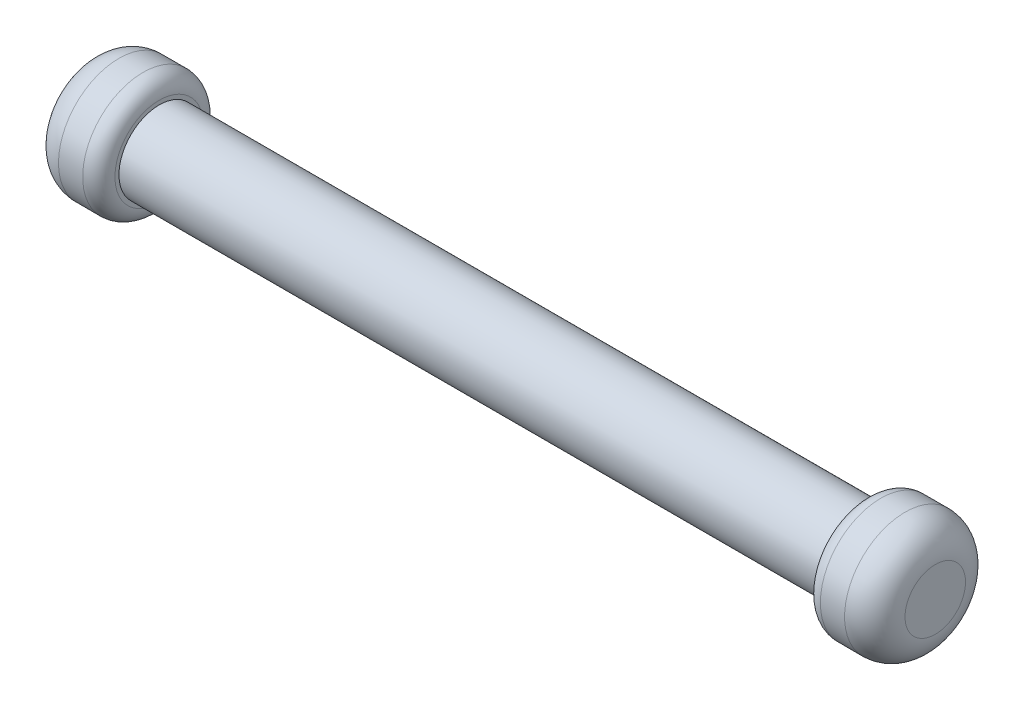
SolidWorks part; units mm, degrees
material "Ст3пс ГОСТ 380-94"
ref_plane "Front Plane" through (0, 0, 0) normal (0, 0, 1) x (1, 0, 0)
ref_plane "Top Plane" through (0, 0, 0) normal (0, 1, 0) x (1, 0, 0)
ref_plane "Right Plane" through (0, 0, 0) normal (1, 0, 0) x (0, 0, -1)
sketch "Эскиз1" plane through (0, 0, 0) normal (0, 0, 1) x (1, 0, 0)
  line L0 (0, 0) -> (0, 3)
  line L1 (0, 3) -> (3.5, 3)
  line L2 (3.5, 3) -> (3.5, 2)
  line L3 (3.5, 2) -> (38.5, 2)
  line L4 (38.5, 2) -> (38.5, 3)
  line L5 (38.5, 3) -> (42, 3)
  line L6 (42, 3) -> (42, 0)
  line L7 (42, 0) -> (0, 0)
  line L8 (0, 0) -> (-3.168, 0) construction
  dimension "D1" = 4
  dimension "D2" = 6
  dimension "D3" = 6
  dimension "D4" = 3.5
  dimension "D5" = 3.5
  dimension "D6" = 35
revolve "Повернуть1" add sketch "Эскиз1" angle 360 about L8
fillet "Скругление1" radius 0.8 2 edges at (38.5, 0, -3) (3.5, 0, -3)
fillet "Скругление2" radius 1.5 2 edges at (42, 0, -3) (0, 0, -3)
